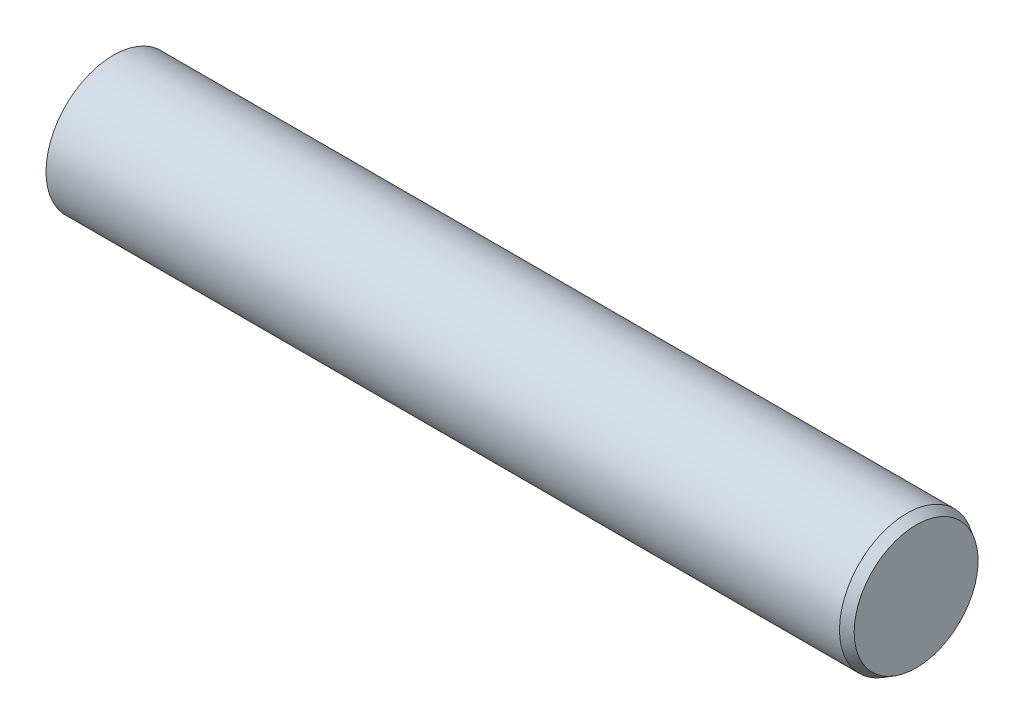
SolidWorks part; units mm, degrees
ref_plane "Front Plane" through (0, 0, 0) normal (0, 0, 1) x (1, 0, 0)
ref_plane "Top Plane" through (0, 0, 0) normal (0, 1, 0) x (1, 0, 0)
ref_plane "Right Plane" through (0, 0, 0) normal (1, 0, 0) x (0, 0, -1)
sketch "Sketch1" plane through (0, 0, 0) normal (0, 0, 1) x (1, 0, 0)
  line L1 (0, 0) -> (30, 0)
  line L2 (0, 0) -> (0, 2.5)
  line L3 (0, 2.5) -> (30, 2.5)
  line L4 (30, 0) -> (30, 2.5)
  dimension "D1" = 30
  dimension "D2" = 2.5
revolve "Revolve1" add sketch "Sketch1" angle 360 about L1
chamfer "Chamfer1" distance 0.2 angle 60 2 edges at (0, 0, 2.5) (30, 0, 2.5)
ref_plane "Plane1" through (15, 0, 0) normal (1, 0, 0) x (0, 0, -1)
